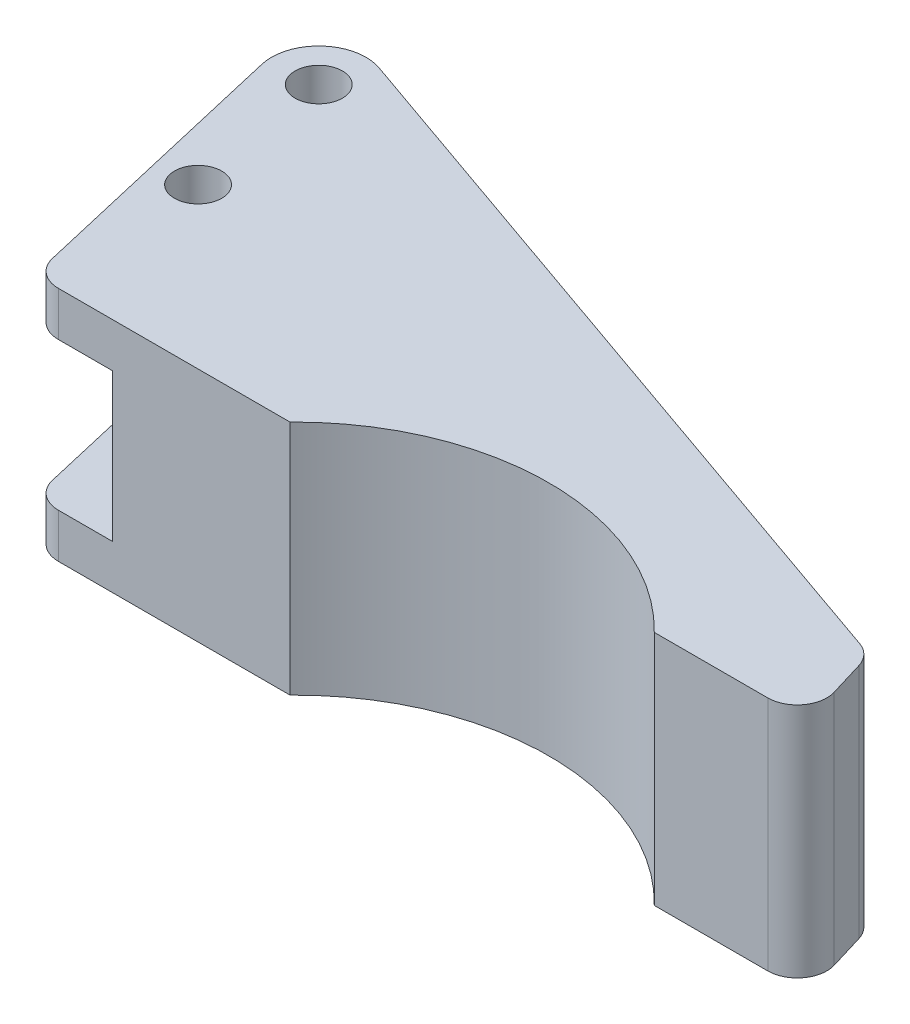
SolidWorks part; units mm, degrees
ref_plane "Front Plane" through (0, 0, 0) normal (0, 0, 1) x (1, 0, 0)
ref_plane "Top Plane" through (0, 0, 0) normal (0, 1, 0) x (1, 0, 0)
ref_plane "Right Plane" through (0, 0, 0) normal (1, 0, 0) x (0, 0, -1)
sketch "Sketch2" plane through (0, 0, 0) normal (0, 1, 0) x (1, 0, 0)
  line L0 (0, 0) -> (-117.8355, 0) construction
  line L1 (-30.8058, 0) -> (-70, 0)
  line L2 (-74.8702, 3.868) -> (-85.6068, 50.0588)
  line L3 (-75.1746, 59.4218) -> (49.837, 15.7199)
  line L4 (52.9732, 12.4463) -> (54.7863, 6.4463)
  line L5 (50, 0) -> (30.8058, 0)
  arc A0 (30.8058, 0) -> (-30.8058, 0) centre (0, -30) ccw
  arc A1 (-70, 0) -> (-74.8702, 3.868) centre (-70, 5) cw
  arc A2 (-75.1746, 59.4218) -> (-85.6068, 50.0588) centre (-77.8146, 51.87) ccw
  arc A3 (52.9732, 12.4463) -> (49.837, 15.7199) centre (48.187, 11) ccw
  arc A4 (54.7863, 6.4463) -> (50, 0) centre (50, 5) cw
  circle A5 centre (-77.8146, 51.87) radius 4
  circle A6 centre (-73.36, 27) radius 4
  point P12 (-73.9711, 0)
  dimension "D2" = 5
  dimension "D3" = 8
  dimension "D4" = 5
  dimension "D7" = 43
  dimension "D10" = 8
  dimension "D1" = 30
  dimension "D5" = 6
  dimension "D6" = 1.65
  dimension "D8" = 3.36
  dimension "D9" = 27
  dimension "D11" = 70
  dimension "D12" = 120
  dimension "D13" = 24.87
extrude "Boss-Extrude1" add sketch "Sketch2" along normal mid plane 40
sketch "Sketch3" plane through (0, 0, 0) normal (0, 0, 1) x (1, 0, 0)
  line L0 (0, 0) -> (-98.9914, 0) construction
  line L2 (-85.8146, 12.5) -> (-60.8146, 12.5)
  line L4 (-85.8146, -12.5) -> (-60.8146, -12.5)
  line L5 (-60.8146, 12.5) -> (-60.8146, -12.5)
  line L8 (-85.8146, 12.5) -> (-85.8146, -12.5)
  point P5 (0, 0)
  dimension "D1" = 25
  dimension "D2" = 25
extrude "Cut-Extrude1" cut sketch "Sketch3" against normal through all
